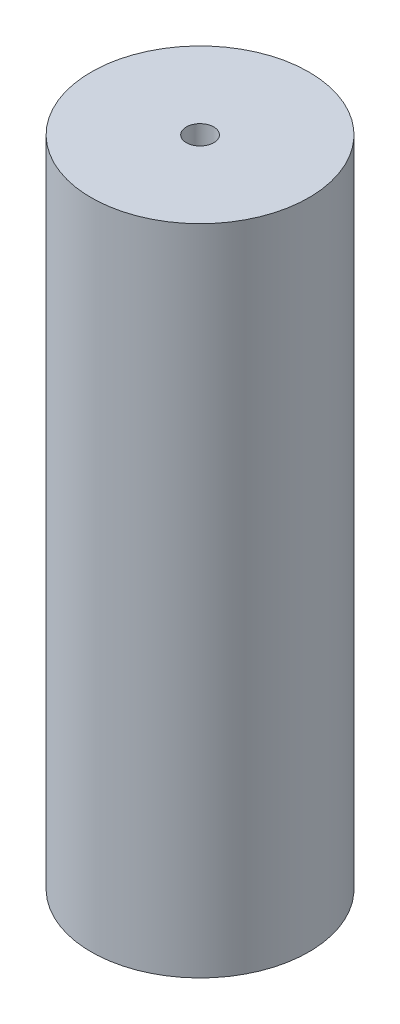
SolidWorks part; units mm, degrees
ref_plane "Front Plane" through (0, 0, 0) normal (0, 0, 1) x (1, 0, 0)
ref_plane "Top Plane" through (0, 0, 0) normal (0, 1, 0) x (1, 0, 0)
ref_plane "Right Plane" through (0, 0, 0) normal (1, 0, 0) x (0, 0, -1)
sketch "Sketch1" plane through (0, 0, 0) normal (0, 1, 0) x (1, 0, 0)
  circle A0 centre (0, 0) radius 6.35
  dimension "D1" = 12.7
extrude "Boss-Extrude1" add sketch "Sketch1" along normal blind 38.1
hole_wizard "M2x0.4 Tapped Hole1" positions "Sketch2" profile "Sketch3" tap size "M2x0.4" standard "ANSI Metric"
sketch "Sketch2" plane through (0, 38.1, 0) normal (0, 1, 0) x (1, 0, 0)
  point P0 (0, 0)
  point P3 (0, 0)
  point P5 (0, 0)
sketch "Sketch3" plane through (0, 38.1, 0) normal (1, 0, 0) x (0, 0, 1)
  line L0 (0, 0) -> (0, 2.5127)
  line L1 (0, 2.5127) -> (0.8, 2.032)
  line L2 (0.8, 2.032) -> (0.8, 0)
  line L5 (0.8, 0) -> (0, 0)
  line L10 (0, 2.5127) -> (-0.8, 2.032) construction
  line L11 (0, -6.35) -> (0, 107.95) construction
  dimension "Tap Drill Dia." = 1.6
  dimension "Tap Drill Depth" = 2.032
  dimension "Drill Angle" = 118
cosmetic thread "Hole Thread1"
